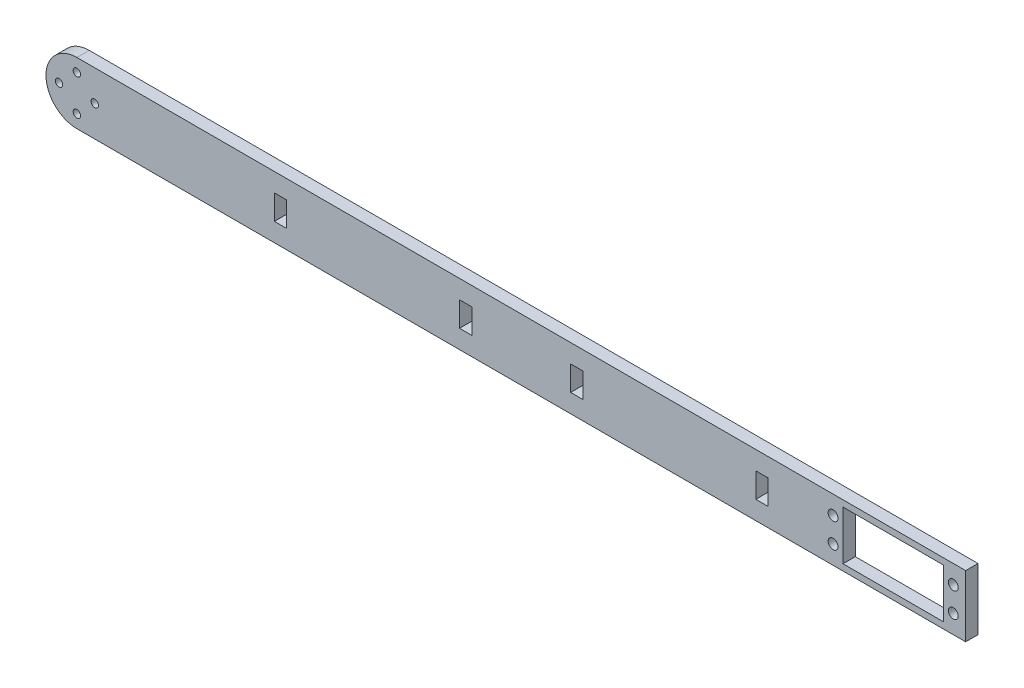
SolidWorks part; units mm, degrees
material "아크릴(내충격성)"
ref_plane "정면" through (0, 0, 0) normal (0, 0, 1) x (1, 0, 0)
ref_plane "윗면" through (0, 0, 0) normal (0, 1, 0) x (1, 0, 0)
ref_plane "우측면" through (0, 0, 0) normal (1, 0, 0) x (0, 0, -1)
sketch "스케치1" plane through (0, 0, 0) normal (0, 0, 1) x (1, 0, 0)
  line L0 (0, -12.5) -> (360, -12.5)
  line L1 (0, 12.5) -> (360, 12.5)
  line L2 (360, 12.5) -> (360, -12.5)
  line L3 (-7.25, 0) -> (7.25, 0)
  arc A0 (0, 12.5) -> (0, -12.5) centre (0, 0) ccw
  circle A2 centre (0, 0) radius 10
  circle A4 centre (0, 7.25) radius 1.5
  circle A5 centre (7.25, 0) radius 1.5
  circle A6 centre (0, -7.25) radius 1.5
  circle A7 centre (-7.25, 0) radius 1.5
  point P22 (0, 0)
  dimension "D1" = 25
  dimension "D3" = 3
  dimension "D5" = 14.5
  dimension "D2" = 360
  dimension "D4" = 4
extrude "보스-돌출1" add sketch "스케치1" along normal blind 5 contours L1 L2 L0 A0 | A7 | A4 | A5 | A6
sketch "스케치4" plane through (0, 0, 5) normal (0, 0, 1) x (1, 0, 0)
  line L2 (351, 9.95) -> (351, -9.95)
  line L3 (351, -9.95) -> (310.3, -9.95)
  line L4 (310.3, -9.95) -> (310.3, 9.95)
  line L5 (310.3, 9.95) -> (351, 9.95)
extrude "컷-돌출1" cut sketch "스케치4" against normal through all
sketch "스케치5" plane through (0, 0, 5) normal (0, 0, 1) x (1, 0, 0)
  circle A0 centre (0, 0) radius 10
  dimension "D1" = 20
sketch "스케치6" plane through (0, 0, 5) normal (0, 0, 1) x (1, 0, 0)
  line L3 (40, 12.5) -> (40, -12.5) construction
  line L4 (0, 12.5) -> (360, 12.5) construction
  line L5 (0, -12.5) -> (360, -12.5) construction
  line L6 (300, 12.5) -> (300, -12.5) construction
  line L29 (80, -5) -> (80, 5)
  line L57 (85, -5) -> (85, 5)
  line L58 (200, -5) -> (200, 5)
  line L59 (155, 5) -> (160, 5)
  line L60 (85, -5) -> (80, -5)
  line L61 (85, 5) -> (80, 5)
  line L62 (155, -5) -> (160, -5)
  line L63 (155, -5) -> (155, 5)
  line L64 (160, -5) -> (160, 5)
  line L65 (205, -5) -> (205, 5)
  line L66 (205, -5) -> (200, -5)
  line L67 (205, 5) -> (200, 5)
  line L68 (275, 5) -> (280, 5)
  line L69 (275, -5) -> (280, -5)
  line L70 (275, -5) -> (275, 5)
  line L71 (280, -5) -> (280, 5)
extrude "컷-돌출2" cut sketch "스케치6" against normal through all
sketch "스케치7" plane through (0, 0, 5) normal (0, 0, 1) x (1, 0, 0)
  circle A0 centre (355, 5) radius 2
  circle A1 centre (355, -5) radius 2
  circle A2 centre (306.3, 5) radius 2
  circle A3 centre (306.3, -5) radius 2
  dimension "D3" = 4
extrude "컷-돌출3" cut sketch "스케치7" against normal through all
